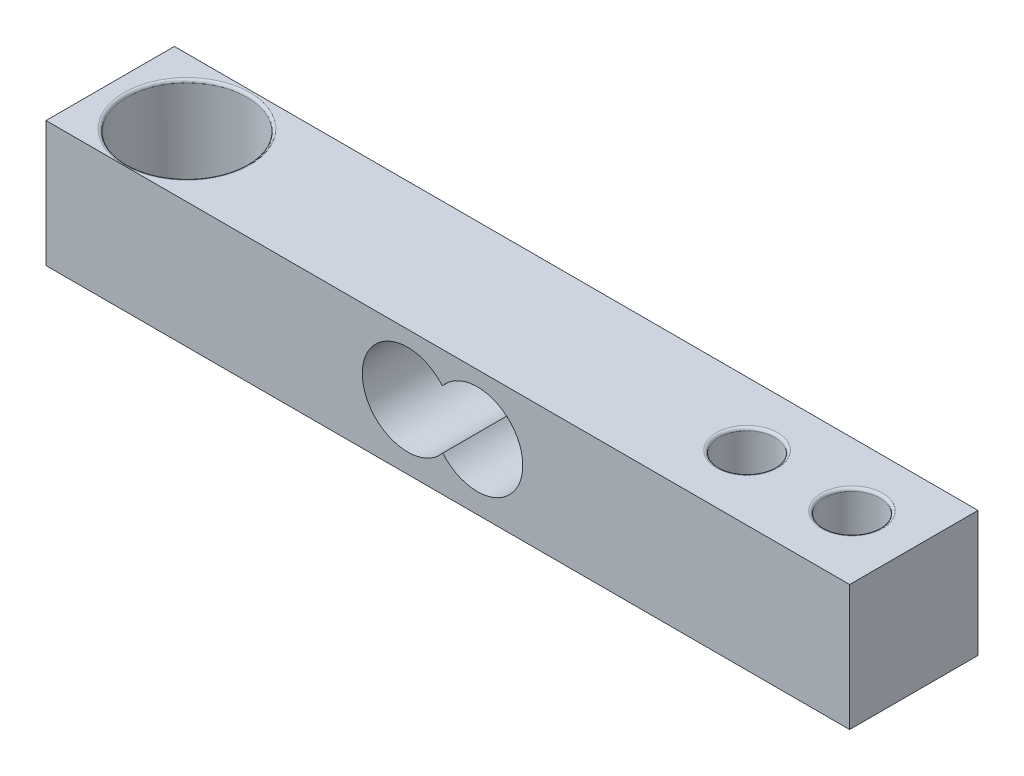
SolidWorks part; units mm, degrees
ref_plane "前视基准面" through (0, 0, 0) normal (0, 0, 1) x (1, 0, 0)
ref_plane "上视基准面" through (0, 0, 0) normal (0, 1, 0) x (1, 0, 0)
ref_plane "右视基准面" through (0, 0, 0) normal (1, 0, 0) x (0, 0, -1)
sketch "草图1" plane through (0, 0, 0) normal (0, 1, 0) x (1, 0, 0)
  line L5 (0, 0) -> (57.5665, 0)
  line L6 (0, 0) -> (0, 9.1946)
  line L7 (0, 9.1946) -> (57.5665, 9.1946)
  line L8 (57.5665, 0) -> (57.5665, 9.1946)
extrude "凸台-拉伸2" add sketch "草图1" along normal blind 9
sketch "草图2" plane through (0, 9, 0) normal (0, 1, 0) x (1, 0, 0)
  circle A0 centre (5.5629, 4.5374) radius 4.3047
extrude "切除-拉伸1" cut sketch "草图2" against normal blind 9
sketch "草图3" plane through (0, 0, 0) normal (0, 0, 1) x (1, 0, 0)
  circle A0 centre (25.9057, 4.6399) radius 3.25
  circle A1 centre (30.9015, 4.6798) radius 3.25
extrude "切除-拉伸4" cut sketch "草图3" against normal through all contours A0 A1 | A1 A0 | A0 A1
sketch "草图4" plane through (0, 9, 0) normal (0, 1, 0) x (1, 0, 0)
  circle A0 centre (45.569, 4.6489) radius 1.9955
  circle A1 centre (53.0827, 4.6489) radius 1.9955
extrude "切除-拉伸5" cut sketch "草图4" against normal through all contours A0 | A1
cosmetic thread "装饰螺纹线4" parameters "D1"=9, "D2"=5
cosmetic thread "装饰螺纹线5" parameters "D1"=9, "D2"=5
fillet "圆角4" radius 0.2 3 edges at (53.0827, 9, -2.6534) (45.569, 9, -2.6534) (5.5629, 9, -0.2327)
